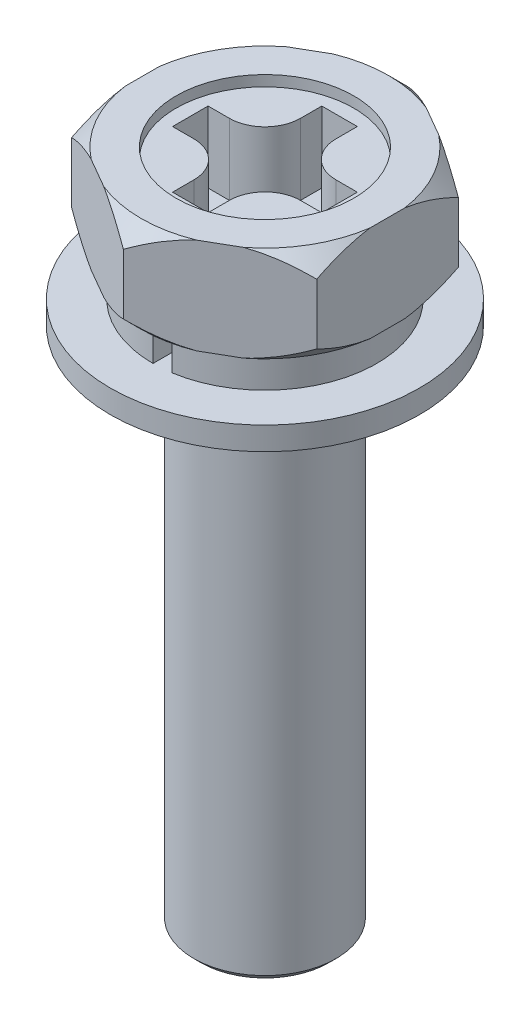
SolidWorks part; units mm, degrees
material "IS 6911 304"
ref_plane "Front" through (0, 0, 0) normal (0, 0, 1) x (1, 0, 0)
ref_plane "Top" through (0, 0, 0) normal (0, 1, 0) x (1, 0, 0)
ref_plane "Right" through (0, 0, 0) normal (1, 0, 0) x (0, 0, -1)
sketch "Sketch2" plane through (0, 0, 0) normal (0, 1, 0) x (1, 0, 0)
  line L1 (0, -3.9837) -> (3.45, -1.9919)
  line L2 (3.45, -1.9919) -> (3.45, 1.9919)
  line L3 (3.45, 1.9919) -> (0, 3.9837)
  line L4 (0, 3.9837) -> (-3.45, 1.9919)
  line L5 (-3.45, 1.9919) -> (-3.45, -1.9919)
  line L6 (-3.45, -1.9919) -> (0, -3.9837)
  circle A0 centre (0, 0) radius 3.45 construction
  dimension "D1" = 6.9
extrude "Boss-Extrude1" add sketch "Sketch2" along normal blind 2.7
sketch "Sketch3" plane through (0, 2.7, 0) normal (0, 1, 0) x (1, 0, 0)
  circle A0 centre (0, 0) radius 2.5
  dimension "D1" = 5
extrude "Cut-Extrude1" cut sketch "Sketch3" against normal blind 0.3
sketch "Sketch4" plane through (0, 0, 0) normal (0, -1, 0) x (1, 0, 0)
  circle A0 centre (0, 0) radius 2
  dimension "D1" = 4
extrude "Boss-Extrude2" add sketch "Sketch4" along normal blind 16.28
sketch "Sketch5" plane through (0, 0, 0) normal (0, -1, 0) x (1, 0, 0)
  line L0 (0, 2.15) -> (0, 3.15)
  line L2 (0.5, 3.1101) -> (0.5, 2.0911)
  arc A0 (0, 2.15) -> (0.5, 2.0911) centre (0, 0) ccw
  arc A1 (0, 3.15) -> (0.5, 3.1101) centre (0, 0) ccw
  circle A3 centre (0, 0) radius 3.15 construction
  circle A4 centre (0, 0) radius 2.15 construction
  point P4 (2.0561, 0.6286)
  point P7 (3.0124, 0.921)
  dimension "D1" = 4.3
  dimension "D3" = 0.5
  dimension "D2" = 1
extrude "Boss-Extrude3" add sketch "Sketch5" along normal blind 1
sketch "Sketch7" plane through (0, -1, 0) normal (0, -1, 0) x (1, 0, 0)
  circle A0 centre (0, 0) radius 4.35
  dimension "D1" = 8.7
extrude "Boss-Extrude4" add sketch "Sketch7" along normal blind 0.65
sketch "Sketch8" plane through (0, 2.4, 0) normal (0, 1, 0) x (1, 0, 0)
  line L1 (-0.5, 2.1) -> (0.5, 2.1)
  line L2 (-0.5, 2.1) -> (-0.5, -2.1)
  line L3 (-0.5, -2.1) -> (0.5, -2.1)
  line L4 (0.5, 2.1) -> (0.5, -2.1)
  line L5 (-0.5, 2.1) -> (0.5, -2.1) construction
  line L6 (-0.5, -2.1) -> (0.5, 2.1) construction
  line L7 (-2.1, 0.5) -> (2.1, 0.5)
  line L8 (-2.1, 0.5) -> (-2.1, -0.5)
  line L9 (-2.1, -0.5) -> (2.1, -0.5)
  line L10 (2.1, 0.5) -> (2.1, -0.5)
  line L11 (-2.1, 0.5) -> (2.1, -0.5) construction
  line L12 (-2.1, -0.5) -> (2.1, 0.5) construction
  point P0 (0, 0)
  point P6 (0, 0)
  dimension "D1" = 1
  dimension "D2" = 4.2
extrude "Cut-Extrude2" cut sketch "Sketch8" against normal blind 2 contours L2 L7 L4 L1 | L2 L9 L4 L7 | L8 L9 L2 L7 | L9 L2 L3 L4 | L10 L7 L4 L9
fillet "Fillet1" radius 1 4 edges at (-0.5, 1.4, -0.5) (-0.5, 1.4, 0.5) (0.5, 1.4, 0.5) (0.5, 1.4, -0.5)
sketch "Sketch9" plane through (0, 0, 0) normal (1, 0, 0) x (0, 0, -1)
  line L0 (-3.9837, 2.7) -> (-3.4837, 2.7)
  line L1 (-3.9837, 2.7) -> (-1.9919, 2.7) construction
  line L2 (-3.4837, 2.7) -> (-3.9837, 2.2)
  line L3 (-3.9837, 2.7) -> (-3.9837, 0) construction
  line L4 (-3.9837, 2.2) -> (-3.9837, 2.7)
  line L5 (-3.9837, 1.35) -> (-1.9919, 1.35) construction
  line L6 (-1.9919, 2.7) -> (-1.9919, 0) construction
  line L7 (-3.9837, 0.5) -> (-3.9837, 0)
  line L8 (-3.4837, 0) -> (-3.9837, 0.5)
  line L9 (-3.9837, 0) -> (-3.4837, 0)
  line L10 (0, 0) -> (0, -16.28) construction
  line L11 (-2, -16.28) -> (2, -16.28) construction
  dimension "D1" = 0.5
revolve "Cut-Revolve1" cut sketch "Sketch9" angle 360 about L10
chamfer "Chamfer1" distance 0.2 angle 45 1 edges at (0, -16.28, -2)
